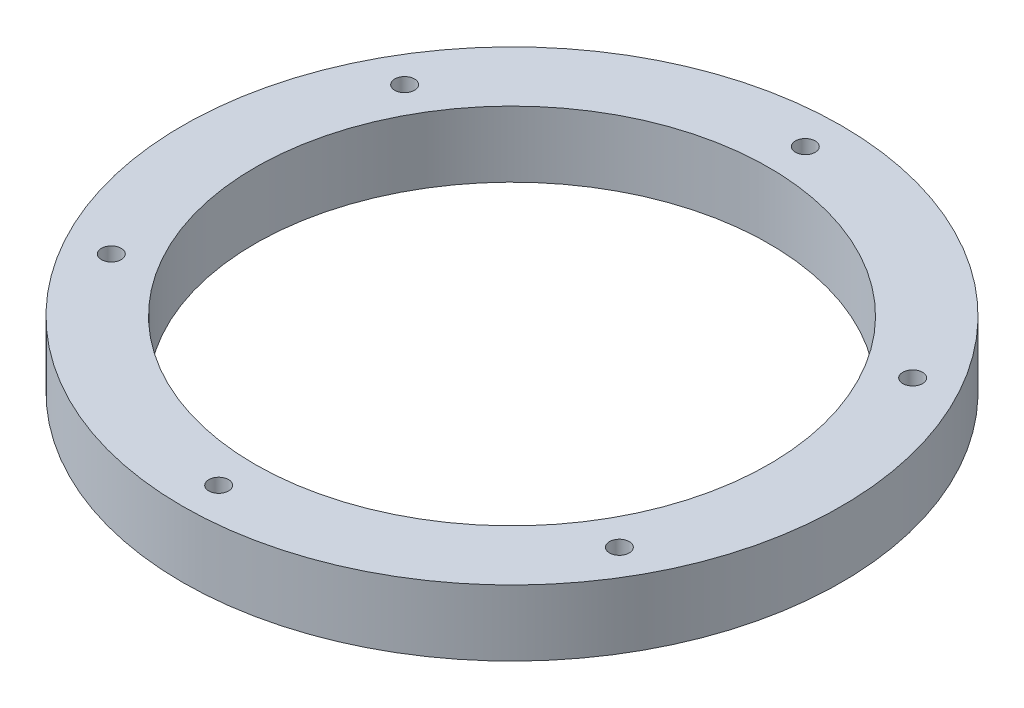
SolidWorks part; units mm, degrees
ref_plane "前视基准面" through (0, 0, 0) normal (0, 0, 1) x (1, 0, 0)
ref_plane "上视基准面" through (0, 0, 0) normal (0, 1, 0) x (1, 0, 0)
ref_plane "右视基准面" through (0, 0, 0) normal (1, 0, 0) x (0, 0, -1)
other "Configuration Table"
sketch "草图1" plane through (0, 0, 0) normal (0, 1, 0) x (1, 0, 0)
  circle A0 centre (0, 0) radius 39
  circle A1 centre (0, 0) radius 50
  dimension "D1" = 78
  dimension "D2" = 100
extrude "凸台-拉伸1" add sketch "草图1" along normal blind 10
sketch "草图2" plane through (0, 10, 0) normal (0, 1, 0) x (1, 0, 0)
  circle A0 centre (0, 0) radius 44.5 construction
  circle A1 centre (0, 44.5) radius 1.5
  circle A2 centre (38.5381, 22.25) radius 1.5
  circle A3 centre (38.5381, -22.25) radius 1.5
  circle A4 centre (0, -44.5) radius 1.5
  circle A5 centre (-38.5381, -22.25) radius 1.5
  circle A6 centre (-38.5381, 22.25) radius 1.5
  point P6 (-52.1454, 24.5983)
  point P7 (0, 0)
  point P17 (0, 0)
  dimension "D1" = 89
  dimension "D2" = 3
  dimension "D3" = 6
extrude "切除-拉伸1" cut sketch "草图2" against normal blind 10
